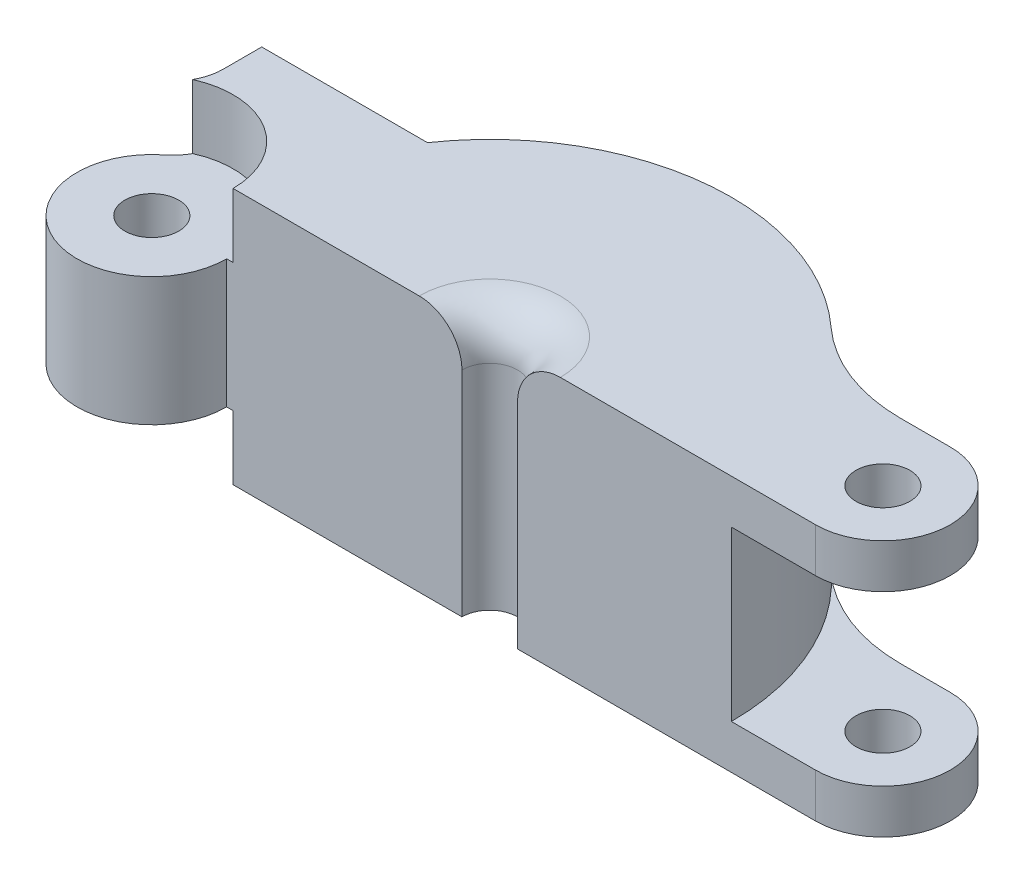
SolidWorks part; units mm, degrees
ref_plane "Front Plane" through (0, 0, 0) normal (0, 0, 1) x (1, 0, 0)
ref_plane "Top Plane" through (0, 0, 0) normal (0, 1, 0) x (1, 0, 0)
ref_plane "Right Plane" through (0, 0, 0) normal (1, 0, 0) x (0, 0, -1)
sketch "Sketch1" plane through (0, 0, 0) normal (0, 1, 0) x (1, 0, 0)
  line L2 (0, 0) -> (0, 14.351) construction
  line L3 (-11.8274, 8.128) -> (-21.67, 8.128)
  line L6 (-21.67, 8.128) -> (-21.67, 4.1471)
  line L7 (14.351, 0) -> (1.651, 0)
  line L10 (14.351, 0) -> (19.351, 0)
  line L11 (-15.625, 0) -> (-1.651, 0)
  line L12 (-20.07, 0) -> (-21.67, 0) construction
  line L13 (19.351, 8) -> (11.9143, 8)
  arc A0 (1.651, 0) -> (-1.651, 0) centre (0, 0) ccw
  arc A1 (11.8274, 8.128) -> (-11.8274, 8.128) centre (0, 0) ccw
  circle A5 centre (-20.07, 0) radius 1.6
  arc A6 (-21.67, 4.1471) -> (-15.625, 0) centre (-20.07, 0) ccw
  arc A7 (11.9143, 8) -> (-11.8274, 8.128) centre (0, 0) ccw
  arc A8 (19.351, 0) -> (19.351, 8) centre (19.351, 4) ccw
  circle A9 centre (19.351, 4) radius 1.6
  dimension "D1" = 3.302
  dimension "D2" = 12.7
  dimension "D5" = 4.445
  dimension "D6" = 3.2
  dimension "D7" = 3.2
  dimension "D8" = 8
  dimension "D3" = 20.07
  dimension "D4" = 8.128
  dimension "D9" = 5
  dimension "D10" = 4
  dimension "D11" = 12.7
extrude "Boss-Extrude1" add sketch "Sketch1" along normal blind 15.24 contours L10 A8 L13 A7 A1 L3 L6 A6 L11 A0 L7 A9 A5
ref_plane "Plane1" through (0, 7.62, 0) normal (0, 1, 0) x (1, 0, 0)
sketch "Sketch2" plane through (0, 15.24, 0) normal (0, 1, 0) x (1, 0, 0)
  circle A0 centre (-20.07, 0) radius 4.826
  dimension "D1" = 9.652
extrude "Cut-Extrude1" cut sketch "Sketch2" against normal mid plane 7.62
fillet "Fillet1" [suppressed] radius 2.54
fillet "Fillet2" radius 2.54 1 edges at (0, 15.24, -1.651)
mirror "Mirror1" about plane through (0, 7.62, 0) normal (0, 1, 0) of "Cut-Extrude1"
fillet "Fillet3" radius 3 1 edges at (-21.67, 7.62, -4.1471)
sketch "Sketch3" plane through (0, 7.62, 0) normal (0, 1, 0) x (1, 0, 0)
  line L0 (4.191, 0) -> (19.351, 0) construction
  line L1 (14.351, 0) -> (19.351, 0)
  line L6 (-15.244, 0) -> (-4.191, 0)
  line L7 (4.191, 0) -> (14.351, 0)
  line L9 (19.351, 8) -> (11.9143, 8)
  line L10 (-11.8274, 8.128) -> (-21.67, 8.128)
  line L11 (-21.67, 8.128) -> (-21.67, 5.8539)
  line L15 (19.351, 8) -> (11.9143, 8)
  arc A0 (14.351, 0) -> (11.9143, 8) centre (0, 0) ccw
  arc A5 (4.191, 0) -> (-4.191, 0) centre (0, 0) ccw
  arc A6 (19.351, 0) -> (19.351, 8) centre (19.351, 4) ccw
  arc A7 (11.9143, 8) -> (-11.8274, 8.128) centre (0, 0) ccw
  arc A8 (-22.0436, 4.404) -> (-21.67, 5.8539) centre (-24.67, 5.8539) ccw
  arc A9 (-15.244, 0) -> (-22.0436, 4.404) centre (-20.07, 0) ccw
  arc A11 (19.351, 0) -> (19.351, 8) centre (19.351, 4) ccw
  dimension "D1" = 0
extrude "Cut-Extrude2" cut sketch "Sketch3" against normal blind 5 and the other way blind 5
fillet "Fillet4" radius 10 2 edges at (11.9143, 1.31, -8) (11.9143, 13.93, -8)
